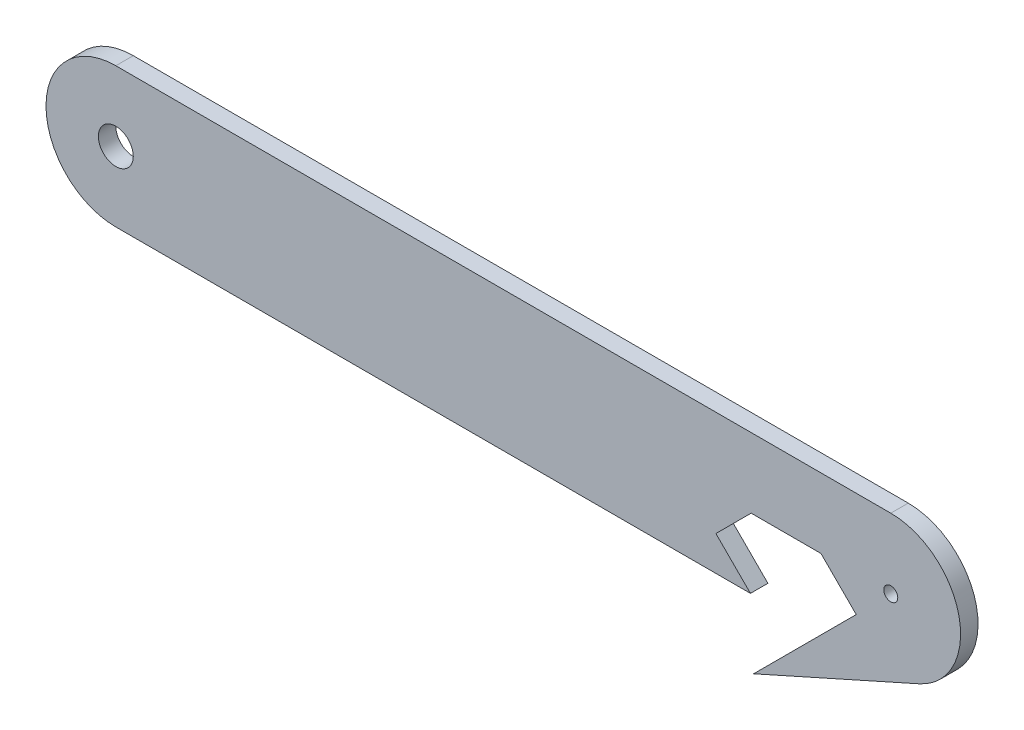
SolidWorks part; units mm, degrees
ref_plane "Front Plane" through (0, 0, 0) normal (0, 0, 1) x (1, 0, 0)
ref_plane "Top Plane" through (0, 0, 0) normal (0, 1, 0) x (1, 0, 0)
ref_plane "Right Plane" through (0, 0, 0) normal (1, 0, 0) x (0, 0, -1)
sketch "Sketch1" plane through (0, 0, 0) normal (0, 0, 1) x (1, 0, 0)
  line L5 (115.57, 0) -> (128.27, 0)
  line L16 (134.6838, -6.4138) -> (128.27, 0)
  line L17 (0, 12.7) -> (140.97, 12.7)
  line L18 (115.57, 0) -> (109.1562, -6.4138)
  line L19 (109.1562, -6.4138) -> (115.4424, -12.7)
  line L20 (0, -12.7) -> (115.4424, -12.7)
  line L23 (134.6838, -6.4138) -> (116.0178, -25.0798)
  line L24 (116.0178, -25.0798) -> (146.1575, -11.5922)
  arc A0 (0, 12.7) -> (0, -12.7) centre (0, 0) ccw
  circle A2 centre (0, 0) radius 3.175
  arc A4 (146.1575, -11.5922) -> (140.97, 12.7) centre (140.97, 0) ccw
  circle A6 centre (140.97, 0) radius 1.27
  dimension "D1" = 25.4
  dimension "D2" = 6.35
  dimension "D3" = 2.54
  dimension "D6" = 12.7
  dimension "D4" = 12.7
  dimension "D5" = 115.57
  dimension "D7" = 8.89
  dimension "D8" = 20.891
  dimension "D9" = 12.7
  dimension "D10" = 9.0705
  dimension "D11" = 33.02
  dimension "D12" = 25.4
extrude "Boss-Extrude1" add sketch "Sketch1" along normal blind 3.175
